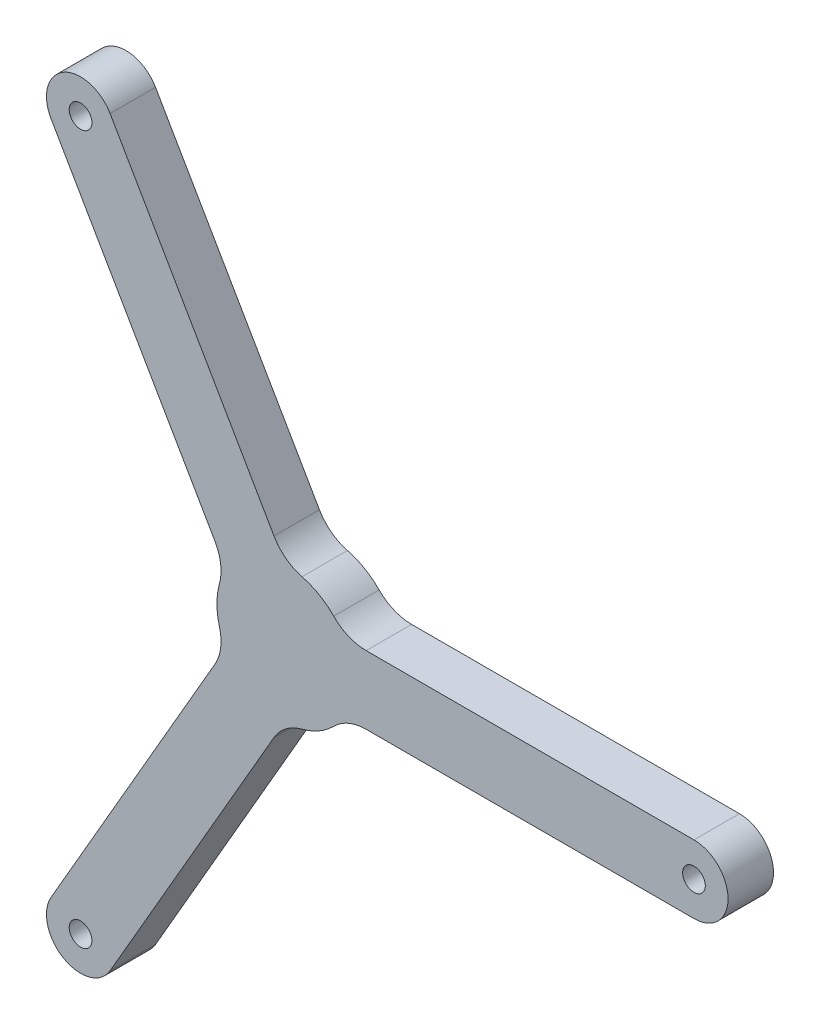
SolidWorks part; units mm, degrees
ref_plane "Front Plane" through (0, 0, 0) normal (0, 0, 1) x (1, 0, 0)
ref_plane "Top Plane" through (0, 0, 0) normal (0, 1, 0) x (1, 0, 0)
ref_plane "Right Plane" through (0, 0, 0) normal (1, 0, 0) x (0, 0, -1)
sketch "Sketch1" plane through (0, 0, 0) normal (0, 0, 1) x (1, 0, 0)
  line L0 (0, 0) -> (90, 0) construction
  line L1 (0, 7.5) -> (90, 7.5)
  line L2 (90, -7.5) -> (12.9904, -7.5)
  circle A0 centre (90, 0) radius 7.5
  circle A1 centre (0, 0) radius 15
  circle A2 centre (90, 0) radius 2.5
  point P11 (90, 0)
  dimension "pin diameter" = 5
  dimension "D1" = 15
  dimension "D2" = 30
  dimension "pin distance" = 90
extrude "Boss-Extrude1" add sketch "Sketch1" along normal blind 10
fillet "Fillet1" radius 10 2 edges at (12.9904, 7.5, 5) (12.9904, -7.5, 5)
pattern_circular "CirPattern2" count 3 over 360 about axis through (0, 0, 0) along (0, 0, 1) of "Boss-Extrude1", "Fillet1"
equation "\"D1@Sketch1\"= \"pin diameter@Sketch1\" + 1"
